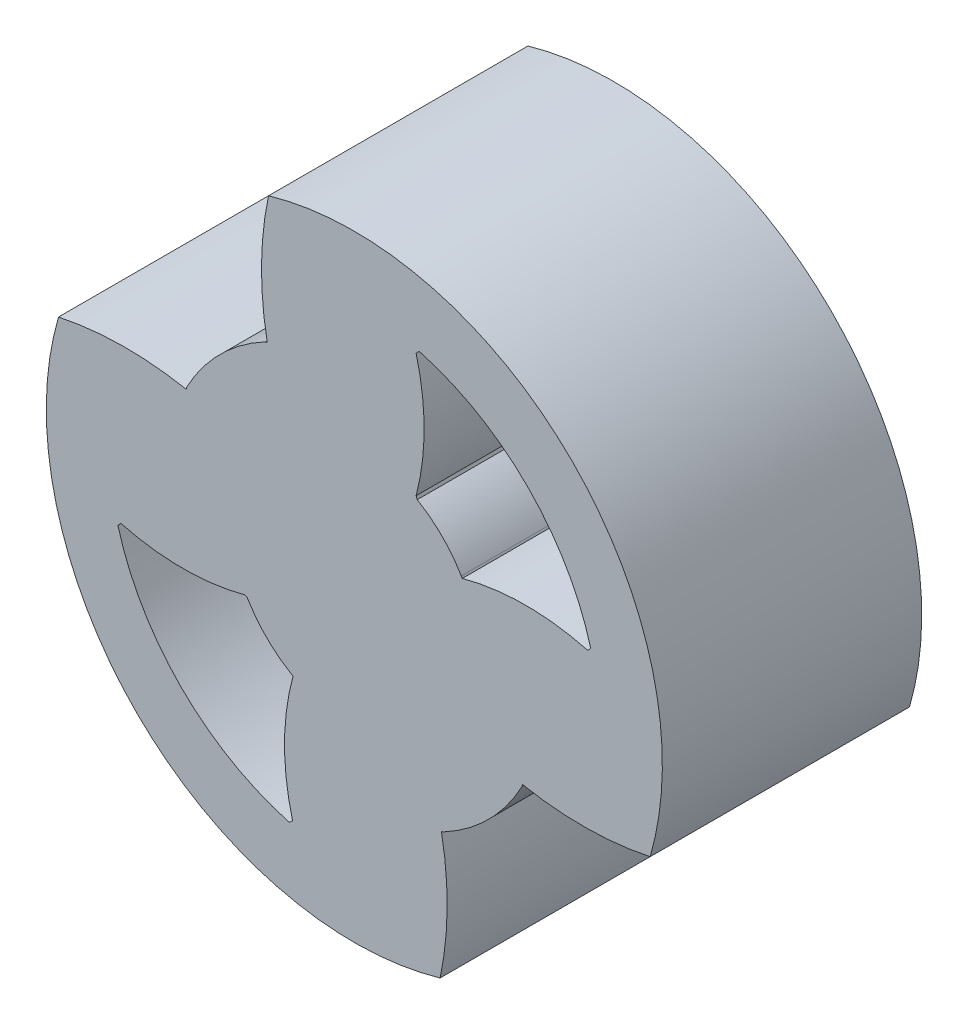
SolidWorks part; units mm, degrees
ref_plane "Front Plane" through (0, 0, 0) normal (0, 0, 1) x (1, 0, 0)
ref_plane "Top Plane" through (0, 0, 0) normal (0, 1, 0) x (1, 0, 0)
ref_plane "Right Plane" through (0, 0, 0) normal (1, 0, 0) x (0, 0, -1)
sketch "Sketch1" plane through (0, 0, 0) normal (0, 0, 1) x (1, 0, 0)
  line L0 (-6.5985, 3.4184) -> (-6.5875, 3.488)
  line L1 (-3.488, 6.5875) -> (-3.4184, 6.5985)
  line L2 (3.4184, -6.5985) -> (3.488, -6.5875)
  line L3 (6.5875, -3.488) -> (6.5985, -3.4184)
  arc A8 (3.3675, -11.6136) -> (3.4184, -6.5985) centre (-8.9803, -8.9803) ccw
  arc A9 (-6.5985, 3.4184) -> (3.4184, -6.5985) centre (0, 0) ccw
  arc A10 (-6.5985, 3.4184) -> (-11.6136, 3.3675) centre (-8.9803, -8.9803) ccw
  arc A11 (-11.6136, 3.3675) -> (3.3675, -11.6136) centre (0, 0) ccw
  arc A12 (3.3675, -11.6136) -> (3.4184, -6.5985) centre (-8.9803, -8.9803) ccw
  arc A14 (-6.5985, 3.4184) -> (-11.6136, 3.3675) centre (-8.9803, -8.9803) ccw
  arc A15 (-11.6136, 3.3675) -> (3.3675, -11.6136) centre (0, 0) ccw
  arc A18 (-3.488, 6.5875) -> (-6.5875, 3.488) centre (0, 0) ccw
  arc A19 (-3.488, 6.5875) -> (-6.5875, 3.488) centre (0, 0) ccw
  arc A20 (-3.3675, 11.6136) -> (-3.4184, 6.5985) centre (8.9803, 8.9803) ccw
  arc A21 (6.5985, -3.4184) -> (-3.4184, 6.5985) centre (0, 0) ccw
  arc A22 (6.5985, -3.4184) -> (11.6136, -3.3675) centre (8.9803, 8.9803) ccw
  arc A23 (11.6136, -3.3675) -> (-3.3675, 11.6136) centre (0, 0) ccw
  arc A24 (-3.3675, 11.6136) -> (-3.4184, 6.5985) centre (8.9803, 8.9803) ccw
  arc A26 (6.5985, -3.4184) -> (11.6136, -3.3675) centre (8.9803, 8.9803) ccw
  arc A27 (11.6136, -3.3675) -> (-3.3675, 11.6136) centre (0, 0) ccw
  arc A29 (3.488, -6.5875) -> (6.5875, -3.488) centre (0, 0) ccw
  arc A30 (3.488, -6.5875) -> (6.5875, -3.488) centre (0, 0) ccw
  dimension "D1" = 0.1
  dimension "D2" = 0.1
  dimension "D3" = 0.1
  dimension "D4" = 0.1
extrude "Boss-Extrude1" add sketch "Sketch1" along normal up to surface (10.1812 mm away)
sketch "Sketch2" plane through (0, 0, 0) normal (0, 0, -1) x (-1, 0, 0)
  circle A0 centre (0, 0) radius 5
  dimension "D1" = 10
extrude "Cut-Extrude1" cut sketch "Sketch2" against normal blind 1
sketch "Sketch3" plane through (0, 0, 10.1812) normal (0, 0, 1) x (1, 0, 0)
  line L0 (9.1595, 2.4252) -> (9.2815, 2.5484)
  line L1 (2.4252, 9.1595) -> (2.5484, 9.2815)
  line L2 (4.2001, 2.4715) -> (4.2387, 2.4058)
  line L3 (2.4715, 4.2001) -> (2.4255, 4.3119)
  arc A5 (2.4255, 4.3119) -> (2.4252, 9.1595) centre (-6.7352, 6.7352) ccw
  arc A6 (2.4255, 4.3119) -> (2.4252, 9.1595) centre (-6.7352, 6.7352) ccw
  arc A11 (9.2815, 2.5484) -> (2.5484, 9.2815) centre (0, 0) ccw
  arc A12 (9.2815, 2.5484) -> (2.5484, 9.2815) centre (0, 0) ccw
  arc A14 (9.1595, 2.4252) -> (8.7382, 2.5265) centre (6.7352, -6.7352) ccw
  arc A15 (9.1595, 2.4252) -> (8.7382, 2.5265) centre (6.7352, -6.7352) ccw
  arc A16 (8.7382, 2.5265) -> (4.0919, 2.3645) centre (6.7352, -6.7352) ccw
  arc A17 (4.2001, 2.4715) -> (2.4715, 4.2001) centre (0, 0) ccw
  arc A18 (4.2001, 2.4715) -> (2.4715, 4.2001) centre (0, 0) ccw
  arc A19 (8.7382, 2.5265) -> (4.2387, 2.4058) centre (6.7352, -6.7352) ccw
  dimension "D1" = 0.1
  dimension "D2" = 0.1
  dimension "D3" = 0.1
  dimension "D4" = 0.1
  dimension "D5" = 0.1
extrude "Cut-Extrude2" cut sketch "Sketch3" against normal blind 7.5
ref_plane "Plane1" through (0, 0, 0) normal (0.7071, 0.7071, 0) x (0.7071, -0.7071, 0)
mirror "Mirror1" about plane through (0, 0, 0) normal (0.7071, 0.7071, 0) of "Cut-Extrude2"
